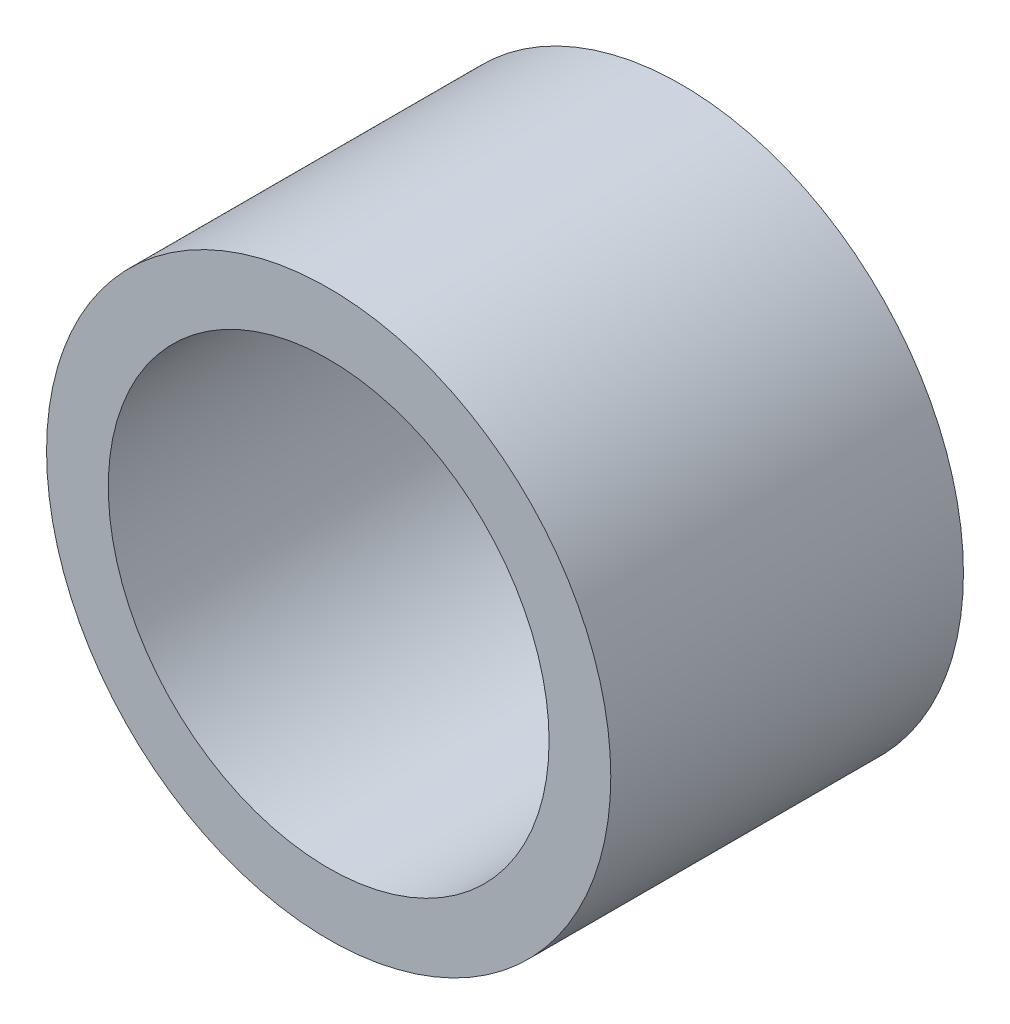
SolidWorks part; units mm, degrees
material "Borracha de silicone"
ref_plane "Plano frontal" through (0, 0, 0) normal (0, 0, 1) x (1, 0, 0)
ref_plane "Plano superior" through (0, 0, 0) normal (0, 1, 0) x (1, 0, 0)
ref_plane "Plano direito" through (0, 0, 0) normal (1, 0, 0) x (0, 0, -1)
sketch "Esboço1" plane through (0, 0, 0) normal (0, 0, 1) x (1, 0, 0)
  circle A0 centre (0, 0) radius 16
  dimension "D1" = 32
extrude "Ressalto-extrusão1" add sketch "Esboço1" along normal blind 20
sketch "Esboço2" plane through (0, 0, 20) normal (0, 0, 1) x (1, 0, 0)
  circle A0 centre (0, 0) radius 12.5
  dimension "D1" = 25
extrude "Corte-extrusão1" cut sketch "Esboço2" against normal blind 20
